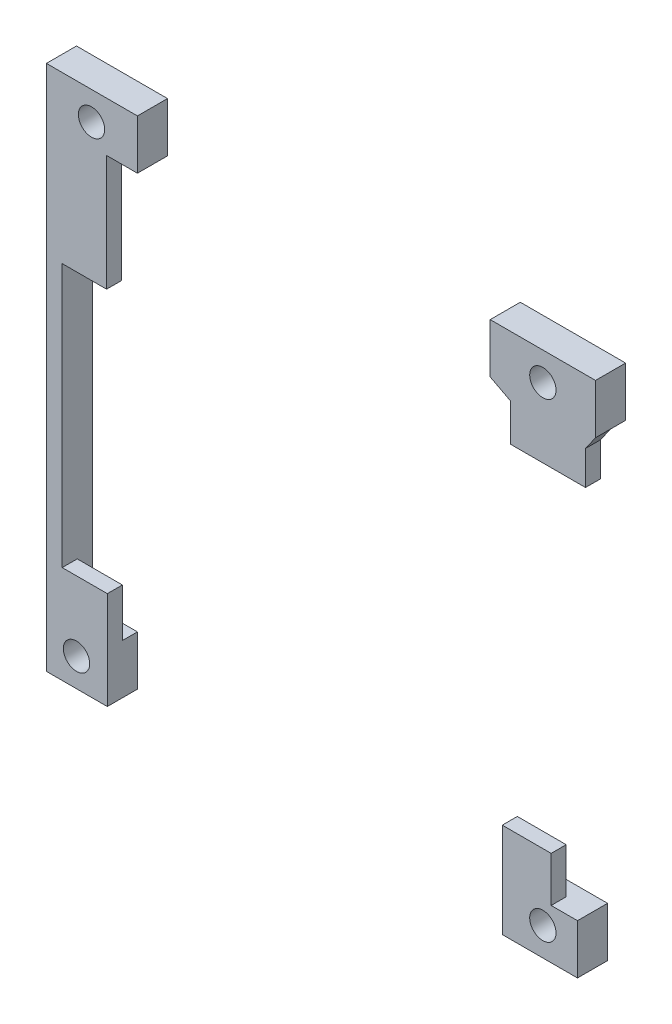
SolidWorks part; units mm, degrees
ref_plane "Front Plane" through (0, 0, 0) normal (0, 0, 1) x (1, 0, 0)
ref_plane "Top Plane" through (0, 0, 0) normal (0, 1, 0) x (1, 0, 0)
ref_plane "Right Plane" through (0, 0, 0) normal (1, 0, 0) x (0, 0, -1)
sketch "Sketch1" plane through (0, 0, 0) normal (0, 0, 1) x (1, 0, 0)
  line L1 (-45, 35) -> (-42.9, 35)
  line L2 (-45, 35) -> (-45, -35)
  line L3 (-45, -35) -> (-42.9, -35)
  line L4 (-42.9, 25.4) -> (-42.9, -25.4)
  line L7 (-42.9, 35) -> (-32.9, 35)
  line L8 (-42.9, 35) -> (-42.9, 28.4) construction
  line L9 (-39.9, 28.4) -> (-32.9, 28.4)
  line L10 (-32.9, 35) -> (-32.9, 28.4)
  line L12 (-42.9, -35) -> (-36.9, -35)
  line L13 (-42.9, -35) -> (-42.9, -28.4) construction
  line L14 (-39.9, -28.4) -> (-36.9, -28.4)
  line L15 (-36.9, -35) -> (-36.9, -28.4)
  line L16 (-42.9, -28.4) -> (-42.9, -35) construction
  line L17 (-42.9, 35) -> (-42.9, 28.4) construction
  arc A0 (-42.9, -25.4) -> (-39.9, -28.4) centre (-39.9, -25.4) ccw
  arc A1 (-42.9, 25.4) -> (-39.9, 28.4) centre (-39.9, 25.4) cw
  circle A2 centre (-39, 31.25) radius 1.75
  circle A3 centre (-41, -31.25) radius 1.75
  dimension "D6" = 3
  dimension "D7" = 3.5
  dimension "D3" = 10
  dimension "D4" = 6
extrude "Boss-Extrude1" add sketch "Sketch1" along normal offset from surface (2 mm away) 0.4
sketch "Sketch2" plane through (0, 0, 2) normal (0, 0, 1) x (1, 0, 0)
  line L0 (-37, 35) -> (-37, 28.4) construction
  line L1 (-45, 35) -> (-37, 35)
  line L2 (-45, 35) -> (-45, 13)
  line L3 (-42.9, 13) -> (-37, 13)
  line L4 (-37, 28.4) -> (-37, 13)
  line L5 (-45, -35) -> (-36.9, -35)
  line L6 (-45, -35) -> (-45, -22)
  line L7 (-42.9, -22) -> (-36.9, -22)
  line L8 (-36.9, -35) -> (-36.9, -22)
  line L9 (-32.9, 28.4) -> (-37, 28.4)
  line L10 (-32.9, 28.4) -> (-32.9, 35)
  line L11 (-32.9, 35) -> (-37, 35)
  line L12 (-37, 28.4) -> (-37, 35) construction
  line L13 (-42.9, -25.4) -> (-42.9, 25.4) construction
  line L14 (-45, 13) -> (-42.9, 13) construction
  line L15 (-45, 13) -> (-45, -22)
  line L16 (-45, -22) -> (-42.9, -22) construction
  line L17 (-42.9, 13) -> (-42.9, -22)
  line L18 (-45, -22) -> (-42.9, -22) construction
  line L19 (-45, 13) -> (-42.9, 13) construction
  circle A0 centre (-41, -31.25) radius 1.75 construction
  circle A1 centre (-39, 31.25) radius 1.75 construction
  circle A2 centre (-41, -31.25) radius 1.75
  circle A3 centre (-39, 31.25) radius 1.75
  dimension "D1" = 13
  dimension "D2" = 8
  dimension "D3" = 22
extrude "Boss-Extrude2" add sketch "Sketch2" along normal blind 2
sketch "Sketch3" plane through (0, 0, 0) normal (0, 0, 1) x (1, 0, 0)
  line L0 (42.9, 35) -> (-45, 35) construction
  line L1 (14, 35) -> (28, 35)
  line L2 (14, 35) -> (14, 28.4)
  line L3 (14, 28.4) -> (28, 28.4)
  line L4 (28, 35) -> (28, 28.4)
  line L5 (39.4, 28) -> (-39.4, 28) construction
  line L6 (21, 31.25) -> (21, 35) construction
  line L7 (-45, -35) -> (42.9, -35) construction
  line L8 (15.6035, -35) -> (25.6035, -35)
  line L9 (15.6035, -35) -> (15.6035, -28.4)
  line L10 (15.6035, -28.4) -> (25.6035, -28.4)
  line L11 (25.6035, -35) -> (25.6035, -28.4)
  line L12 (-39.4, -28) -> (39.4, -28) construction
  line L13 (14.6035, -27.958) -> (14.6035, -27.458) construction
  circle A0 centre (21, 31.25) radius 1.75
  circle A1 centre (21, -31.25) radius 1.75
  dimension "D3" = 3.5
  dimension "D4" = 3.5
  dimension "D1" = 0.4
  dimension "D2" = 14
  dimension "D5" = 0.4
  dimension "D6" = 1
  dimension "D7" = 10
extrude "Boss-Extrude3" add sketch "Sketch3" along normal up to surface (2 mm away) separate body up to face at (-40.0243, -25.3643, 2)
sketch "Sketch4" plane through (0, 0, 2) normal (0, 0, 1) x (1, 0, 0)
  line L0 (28, 35) -> (28, 28.4)
  line L1 (28, 28.4) -> (26.6696, 26.5)
  line L2 (26.6696, 26.5) -> (26.6696, 22)
  line L3 (26.6696, 22) -> (16.6696, 22)
  line L4 (16.6696, 22) -> (16.6696, 27)
  line L5 (16.6696, 27) -> (14, 28.4)
  line L6 (14, 35) -> (14, 28.4) construction
  line L7 (14, 28.4) -> (28, 28.4) construction
  line L8 (14, 28.4) -> (14, 35)
  line L9 (14, 35) -> (28, 35)
  line L10 (15.6035, -35) -> (15.6035, -28.4)
  line L11 (15.6035, -28.4) -> (15.6035, -22.4)
  line L12 (15.6035, -22.4) -> (22.1035, -22.4)
  line L13 (22.1035, -22.4) -> (22.1035, -28.4)
  line L14 (25.6035, -28.4) -> (15.6035, -28.4) construction
  line L15 (22.1035, -28.4) -> (25.6035, -28.4)
  line L16 (25.6035, -28.4) -> (25.6035, -35)
  line L17 (25.6035, -35) -> (15.6035, -35)
  circle A0 centre (21, 31.25) radius 1.75
  circle A1 centre (21, -31.25) radius 1.75
  dimension "D1" = 3.5
  dimension "D7" = 3.5
  dimension "D2" = 10
  dimension "D3" = 145
  dimension "D4" = 4.5
  dimension "D5" = 5
  dimension "D6" = 1.4
  dimension "D8" = 6
  dimension "D9" = 6.5
extrude "Boss-Extrude4" add sketch "Sketch4" along normal up to surface (2 mm away) up to face at (-39.25, -31.25, 4)
